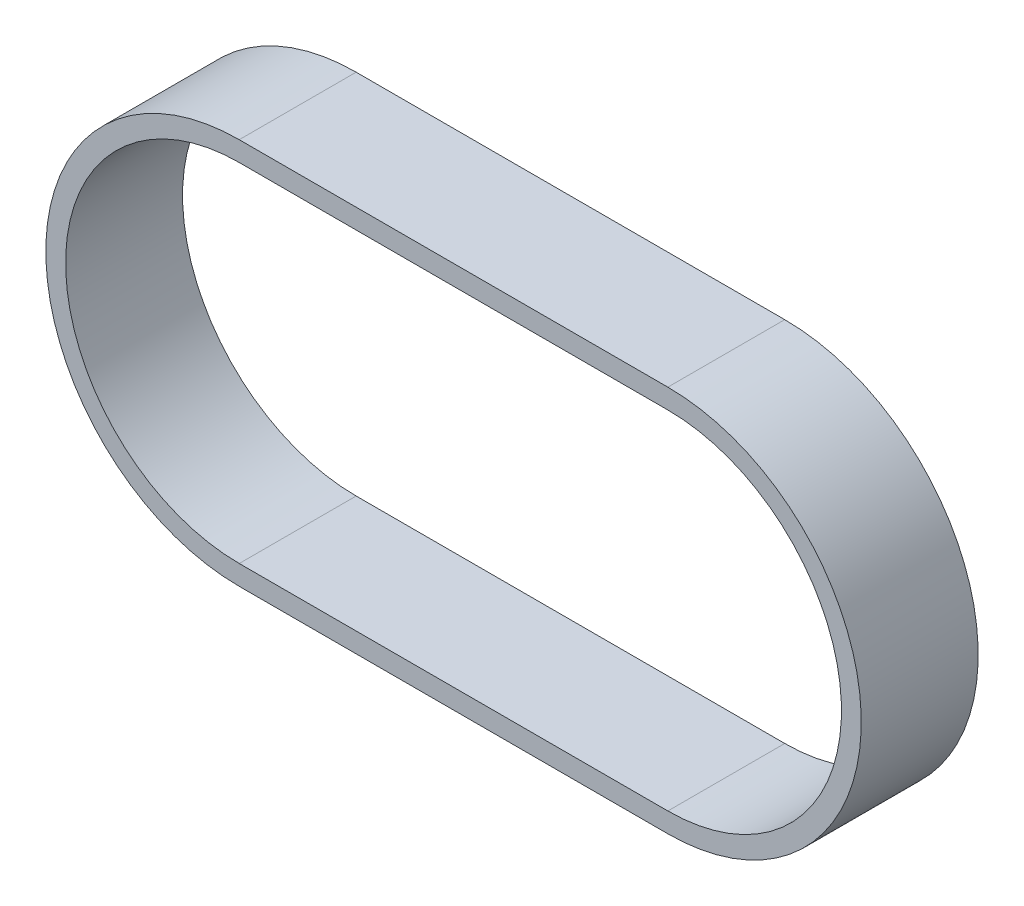
SolidWorks part; units mm, degrees
ref_plane "Front Plane" through (0, 0, 0) normal (0, 0, 1) x (1, 0, 0)
ref_plane "Top Plane" through (0, 0, 0) normal (0, 1, 0) x (1, 0, 0)
ref_plane "Right Plane" through (0, 0, 0) normal (1, 0, 0) x (0, 0, -1)
sketch "Sketch1" plane through (0, 0, 0) normal (0, 0, 1) x (1, 0, 0)
  line L0 (54.991, 0) -> (0, 0) construction
  line L1 (0, 22.2758) -> (54.991, 22.2758)
  line L2 (54.991, -22.2758) -> (0, -22.2758)
  line L3 (27.4955, 22.2758) -> (27.4955, 2.5582) construction
  line L4 (0, 24.8158) -> (54.991, 24.8158)
  line L5 (54.991, -24.8158) -> (0, -24.8158)
  circle A0 centre (0, 0) radius 22.2758 construction
  circle A1 centre (54.991, 0) radius 22.2758 construction
  arc A2 (0, -22.2758) -> (0, 22.2758) centre (0, 0) cw
  arc A3 (54.991, -22.2758) -> (54.991, 22.2758) centre (54.991, 0) ccw
  arc A4 (54.991, -24.8158) -> (54.991, 24.8158) centre (54.991, 0) ccw
  arc A5 (0, -24.8158) -> (0, 24.8158) centre (0, 0) cw
  dimension "D1" = 44.5516
  dimension "D2" = 54.991
  dimension "D3" = 2.54
extrude "Boss-Extrude1" add sketch "Sketch1" along normal blind 15
